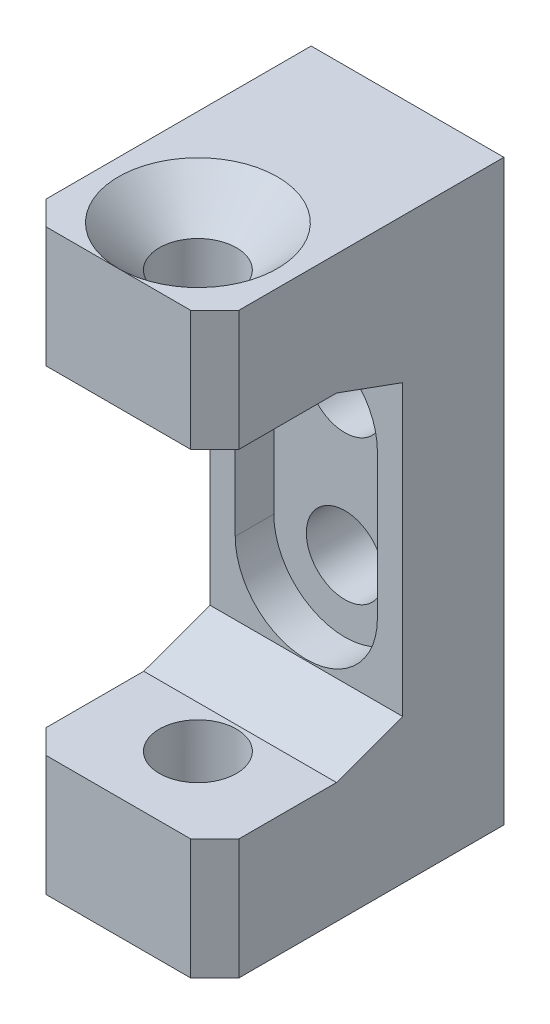
SolidWorks part; units mm, degrees
ref_plane "前视基准面" through (0, 0, 0) normal (0, 0, 1) x (1, 0, 0)
ref_plane "上视基准面" through (0, 0, 0) normal (0, 1, 0) x (1, 0, 0)
ref_plane "右视基准面" through (0, 0, 0) normal (1, 0, 0) x (0, 0, -1)
sketch "草图2" plane through (0, 0, 0) normal (0, 0, 1) x (1, 0, 0)
  line L0 (72, 105) -> (127, 105) construction
  line L1 (101, 105) -> (93, 105)
  line L2 (101, 105) -> (101, 81)
  line L3 (101, 81) -> (93, 81)
  line L4 (93, 105) -> (93, 81)
  line L6 (97, 81) -> (97, 105) construction
  line L7 (127, 105) -> (127, -105) construction
  dimension "D1" = 24
  dimension "D2" = 8
  dimension "D3" = 30
extrude "凸台-拉伸1" add sketch "草图2" along normal blind 12
sketch "草图3" plane through (93, 0, 0) normal (-1, 0, 0) x (0, 0, 1)
  line L0 (0, 93) -> (22.6575, 93) construction
  line L5 (0, 105) -> (0, 81) construction
  line L6 (12, 81) -> (0, 81) construction
  line L7 (4.2, 100) -> (13.3805, 100)
  line L8 (4.2, 100) -> (4.2, 86)
  line L9 (4.2, 86) -> (13.3805, 86)
  line L10 (13.3805, 100) -> (13.3805, 86)
  line L11 (4.2, 100) -> (13.3805, 86) construction
  line L12 (4.2, 86) -> (13.3805, 100) construction
  point P0 (8.7902, 93)
  dimension "D1" = 4.2
  dimension "D2" = 5
extrude "切除-拉伸1" cut sketch "草图3" against normal blind 40
sketch "草图4" plane through (0, 0, 4.2) normal (0, 0, 1) x (1, 0, 0)
  line L0 (97, 100) -> (97, 86) construction
  line L1 (101, 100) -> (93, 100) construction
  line L2 (101, 86) -> (93, 86) construction
  line L3 (97, 93) -> (101, 93) construction
  line L4 (101, 100) -> (101, 86) construction
  circle A0 centre (97, 96) radius 2
  circle A1 centre (97, 90) radius 2
  dimension "D1" = 4
  dimension "D2" = 6
chamfer "倒角1" distance 1 angle 70 2 edges at (97, 86, 4.2) (97, 100, 4.2)
sketch "草图6" plane through (0, 105, 0) normal (0, 1, 0) x (1, 0, 0)
  line L0 (97, -6.9475) -> (97, -12) construction
  line L4 (101, -12) -> (101, -6.9475)
  line L5 (101, -6.9475) -> (93, -6.9475)
  line L6 (93, -6.9475) -> (93, -12)
  line L7 (93, -12) -> (101, -12)
  line L8 (101, -12) -> (101, -6.9475) construction
  line L9 (101, -6.9475) -> (93, -6.9475) construction
  line L10 (93, -6.9475) -> (93, -12) construction
  line L11 (93, -12) -> (101, -12) construction
  circle A1 centre (97, -8.7) radius 1.5
  dimension "D2" = 3
  dimension "D3" = 3.3
  dimension "D1" = 0
hole_wizard "M3 六角头螺栓的柱形沉头孔1" positions "草图7" profile "草图8" counterbore size "M3" standard "GB" end condition through all
sketch "草图7" plane through (124.3639, -131.0101, 4.2) normal (0, 0, 1) x (0, 1, 0)
  point P0 (221.0101, 27.3639)
  point P3 (227.0101, 27.3639)
sketch "草图8" plane through (97, 90, 4.2) normal (1, 0, 0) x (0, -1, 0)
  line L0 (0, 0) -> (0, 4.2)
  line L1 (0, 4.2) -> (1.6, 4.2)
  line L2 (1.6, 4.2) -> (1.6, 1.6)
  line L3 (1.6, 1.6) -> (2.95, 1.6)
  line L4 (2.95, 1.6) -> (2.95, 0)
  line L5 (2.95, 0) -> (0, 0)
  line L6 (0, -6.35) -> (0, 107.95) construction
  dimension "通孔孔直径" = 3.2
  dimension "通孔孔深度" = 4.2
  dimension "柱形沉头孔直径" = 5.9
  dimension "柱形沉头孔深度" = 1.6
sketch "草图11" plane through (0, 0, 4.2) normal (0, 0, 1) x (1, 0, 0)
  line L0 (97, 90) -> (97, 96) construction
  line L1 (94.05, 90) -> (94.05, 96)
  line L2 (99.95, 90) -> (99.95, 96)
  arc A0 (94.05, 90) -> (99.95, 90) centre (97, 90) ccw
  arc A1 (99.95, 96) -> (94.05, 96) centre (97, 96) ccw
  point P2 (97, 93)
  dimension "D1" = 5.9
extrude "切除-拉伸2" cut sketch "草图11" against normal up to surface (1.6 mm away) up to face at (98.6, 90, 2.6)
hole_wizard "打孔尺寸(%根据十字)槽沉头木螺钉的类型" positions "草图12" profile "草图13" countersink size "M3" standard "GB"
sketch "草图12" plane through (124.3639, 105, -5) normal (0, 1, 0) x (-1, 0, 0)
  point P0 (27.3639, 13.7)
sketch "草图13" plane through (97, 105, 8.7) normal (1, 0, 0) x (0, 0, 1)
  line L0 (0, 0) -> (0, 24.9614)
  line L1 (0, 24.9614) -> (1.6, 24)
  line L2 (1.6, 24) -> (1.6, 1.7)
  line L3 (1.6, 1.7) -> (3.3, 0)
  line L4 (3.3, 0) -> (0, 0)
  line L5 (-1.6, 1.7) -> (-3.3, 0) construction
  line L6 (0, 24.9614) -> (-1.6, 24) construction
  line L7 (0, -6.35) -> (0, 107.95) construction
  dimension "孔直径" = 3.2
  dimension "孔深度" = 24
  dimension "近端锥形沉头孔直径" = 6.6
  dimension "近端锥形沉头孔角度" = 90
  dimension "导头角度" = 118
chamfer "倒角2" distance 1 angle 45 4 edges at (93, 83.5, 12) (101, 83.5, 12) (101, 102.5, 12) (93, 102.5, 12)
